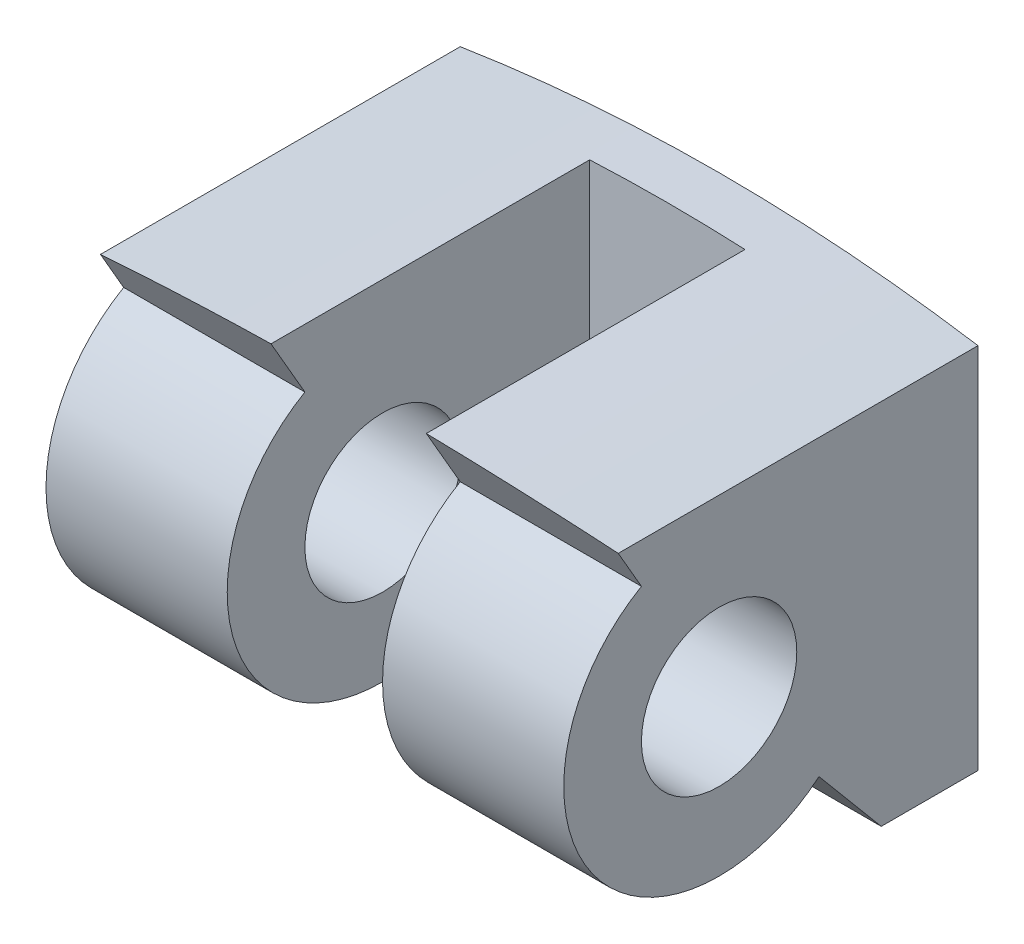
SolidWorks part; units mm, degrees
ref_plane "Alzado" through (0, 0, 0) normal (0, 0, 1) x (1, 0, 0)
ref_plane "Planta" through (0, 0, 0) normal (0, 1, 0) x (1, 0, 0)
ref_plane "Vista lateral" through (0, 0, 0) normal (1, 0, 0) x (0, 0, -1)
sketch "Croquis1" plane through (0, 0, 0) normal (0, 0, 1) x (1, 0, 0)
  line L2 (-5, 31.607) -> (-5, 24.5)
  line L3 (-5, 24.5) -> (5, 24.5)
  line L4 (5, 31.607) -> (5, 24.5)
  circle A0 centre (0, 0) radius 32 construction
  arc A1 (-5, 31.607) -> (5, 31.607) centre (0, 0) cw
  point P11 (0, 32)
  dimension "D1" = 64
  dimension "D2" = 7.5
  dimension "D3" = 10
extrude "Saliente-Extruir1" add sketch "Croquis1" along normal blind 8
sketch "Croquis2" plane through (0, 24.5, 0) normal (0, -1, 0) x (1, 0, 0)
  line L0 (0, 0) -> (0, 8) construction
  line L1 (-5, 0) -> (5, 0) construction
  line L2 (-5, 8) -> (5, 8) construction
  line L4 (1.5, 1) -> (-1.5, 1)
  line L5 (1.5, 1) -> (1.5, 8)
  line L6 (1.5, 8) -> (-1.5, 8)
  line L7 (-1.5, 1) -> (-1.5, 8)
  line L8 (1.5, 1) -> (-1.5, 8) construction
  line L9 (1.5, 8) -> (-1.5, 1) construction
  point P6 (0, 4.5)
  dimension "D1" = 1
  dimension "D2" = 3
extrude "Cortar-Extruir1" cut sketch "Croquis2" against normal blind 10
sketch "Croquis3" plane through (-1.5, 0, 0) normal (1, 0, 0) x (0, 0, -1)
  line L0 (-8, 28.2324) -> (-1, 28.2324) construction
  line L4 (-8, 31.9648) -> (-8, 24.5)
  line L5 (-8, 24.5) -> (-1, 24.5)
  line L6 (-1, 24.5) -> (-1, 31.9648)
  line L7 (-1, 31.9648) -> (-8, 31.9648)
  line L8 (-8, 31.9648) -> (-8, 24.5)
  line L9 (-8, 24.5) -> (-1, 24.5)
  line L10 (-1, 24.5) -> (-1, 31.9648)
  line L11 (-1, 31.9648) -> (-8, 31.9648)
  circle A0 centre (-5, 28.2324) radius 1.5
  dimension "D2" = 3
  dimension "D3" = 3
  dimension "D1" = 0
extrude "Cortar-Extruir3" cut sketch "Croquis3" against normal up to surface and the other way up to surface up to face at (-5, 28.0535, 4) other way up to face at (5, 28.0535, 4)
ref_axis "Eje1" through (1.5, 28.2324, 5) along (1, 0, 0)
ref_plane "Plano1" through (0, 28.2324, 0) normal (0, 1, 0) x (1, 0, 0)
sketch "Croquis6" plane through (0, 28.2324, 0) normal (0, 1, 0) x (1, 0, 0)
  line L1 (5, -6.5) -> (5, -3.5) construction
  line L15 (-5, -31.1268) -> (-5, -24.1278)
  line L16 (5, -6.5) -> (5, -3.5)
  line L17 (-5, -8) -> (-5, 0) construction
  line L18 (-5, -8) -> (-5, 0)
  line L20 (5, -5) -> (-5, -5)
  line L21 (5, -5) -> (5, -8)
  line L22 (5, -8) -> (-5, -8)
  line L23 (-5, -5) -> (-5, -8)
  line L24 (-5, -8) -> (5, -8)
  line L25 (-5, -8) -> (-5, -15)
  line L26 (-5, -15) -> (5, -15)
  line L27 (5, -8) -> (5, -15)
  dimension "D1" = 3
  dimension "D2" = 10
revolve "Cortar-Revolución4" cut sketch "Croquis6" angle 130 about axis through (1.5, 28.2324, 5) along (1, 0, 0) other way angle 60
sketch "Croquis7" plane through (0, 0, 1) normal (0, 0, 1) x (1, 0, 0)
  line L0 (0, 32) -> (0, 29) construction
  arc A0 (1.5, 31.9648) -> (-1.5, 31.9648) centre (0, 0) ccw construction
  circle A1 centre (0, 29) radius 0.5
  dimension "D2" = 1
  dimension "D1" = 3
extrude "Cortar-Extruir4" cut sketch "Croquis7" against normal blind 10
